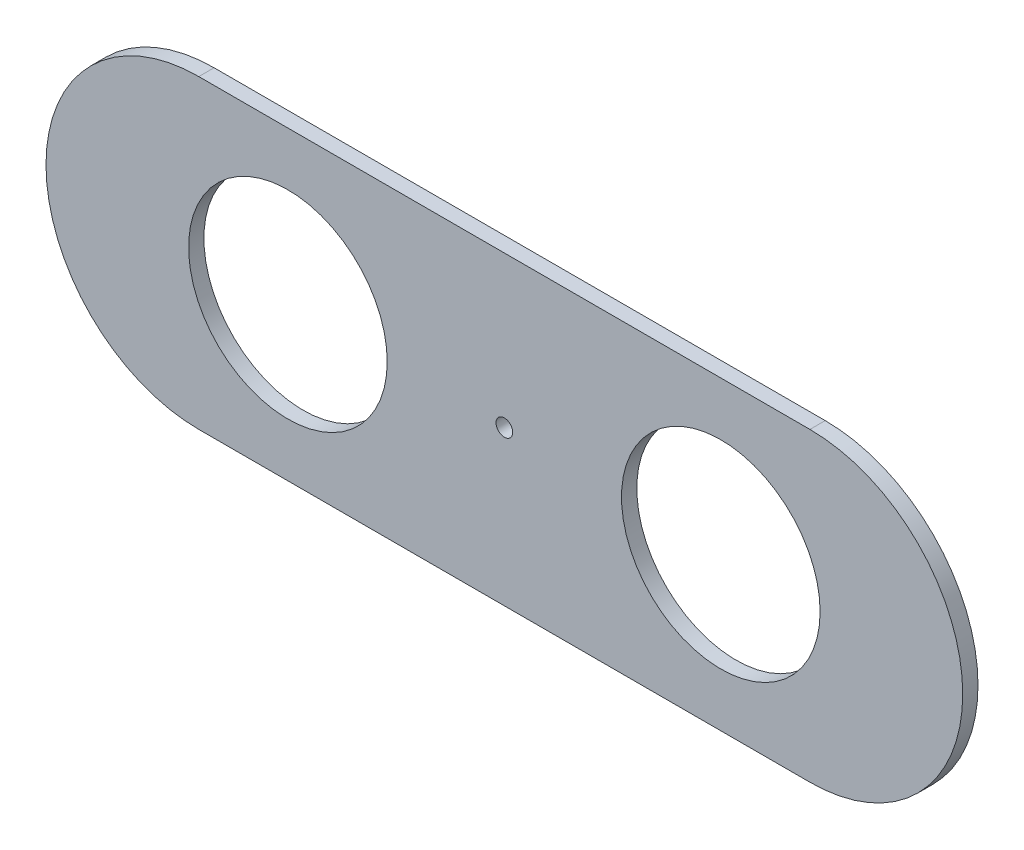
SolidWorks part; units mm, degrees
ref_plane "Plan de face" through (0, 0, 0) normal (0, 0, 1) x (1, 0, 0)
ref_plane "Plan de dessus" through (0, 0, 0) normal (0, 1, 0) x (1, 0, 0)
ref_plane "Plan de droite" through (0, 0, 0) normal (1, 0, 0) x (0, 0, -1)
sketch "Esquisse2" plane through (0, 0, 0) normal (0, 0, 1) x (1, 0, 0)
  line L0 (120, 0) -> (-120, 0) construction
  line L3 (120, -60) -> (-120, -60)
  line L4 (120, 60) -> (-120, 60)
  arc A2 (120, -60) -> (120, 60) centre (120, 0) ccw
  arc A3 (-120, 60) -> (-120, -60) centre (-120, 0) ccw
  point P2 (0, 0)
  dimension "D1" = 240
  dimension "D2" = 120
extrude "Boss.-Extru.1" add sketch "Esquisse2" along normal blind 6
sketch "Esquisse3" plane through (0, 0, 6) normal (0, 0, 1) x (1, 0, 0)
  circle A0 centre (0, 0.625) radius 3.275
  dimension "D1" = 6.55
extrude "Enlèv. mat.-Extru.1" cut sketch "Esquisse3" against normal up to next
sketch "Esquisse4" plane through (0, 0, 6) normal (0, 0, 1) x (1, 0, 0)
  circle A0 centre (-85, 0) radius 39
  circle A1 centre (85, 0) radius 39
extrude "Enlèv. mat.-Extru.2" cut sketch "Esquisse4" against normal up to next
